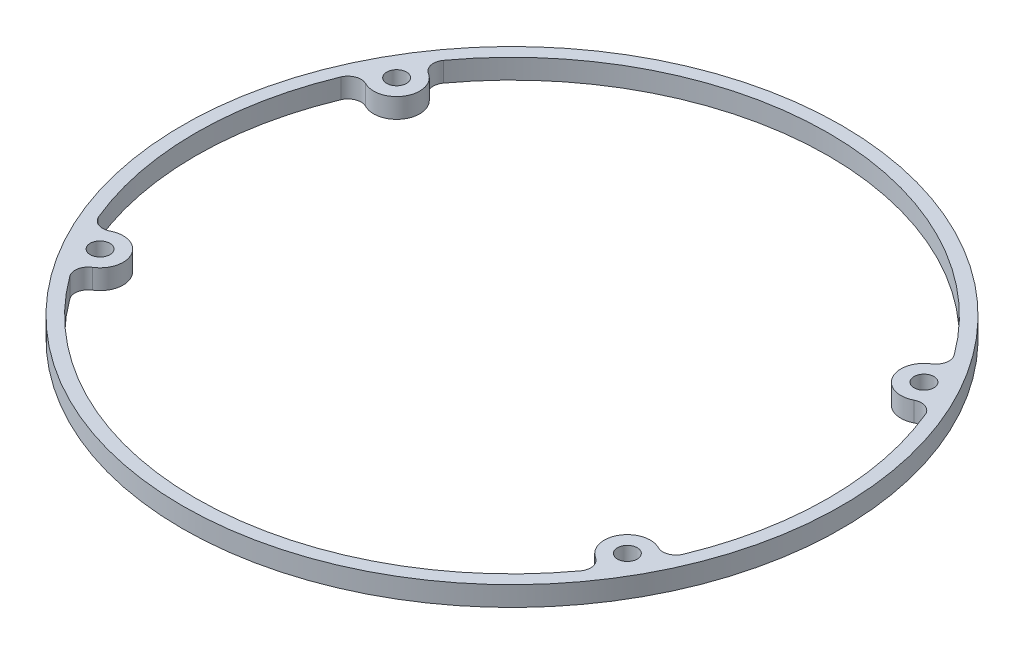
SolidWorks part; units mm, degrees
material "Cast Alloy Steel"
ref_plane "Front Plane" through (0, 0, 0) normal (0, 0, 1) x (1, 0, 0)
ref_plane "Top Plane" through (0, 0, 0) normal (0, 1, 0) x (1, 0, 0)
ref_plane "Right Plane" through (0, 0, 0) normal (1, 0, 0) x (0, 0, -1)
sketch "Sketch1" plane through (0, 0, 0) normal (0, 1, 0) x (1, 0, 0)
  line L1 (40, -22.5) -> (-40, -22.5) construction
  line L2 (40, -22.5) -> (40, 22.5) construction
  line L3 (40, 22.5) -> (-40, 22.5) construction
  line L4 (-40, -22.5) -> (-40, 22.5) construction
  line L5 (40, -22.5) -> (-40, 22.5) construction
  line L6 (40, 22.5) -> (-40, -22.5) construction
  circle A0 centre (0, 0) radius 50
  circle A1 centre (-40, 22.5) radius 1.5
  circle A2 centre (40, 22.5) radius 1.5
  circle A3 centre (40, -22.5) radius 1.5
  circle A4 centre (-40, -22.5) radius 1.5
  dimension "D1" = 100
  dimension "D4" = 3
  dimension "D2" = 80
  dimension "D3" = 45
extrude "Boss-Extrude1" add sketch "Sketch1" along normal blind 3
sketch "Sketch2" plane through (0, 0, 0) normal (0, -1, 0) x (1, 0, 0)
  arc A0 (38.7247, 28.362) -> (-38.7247, 28.362) centre (0, 0) ccw
  circle A1 centre (0, 0) radius 50 construction
  arc A2 (38.1616, 25.4783) -> (41.5906, 19.3823) centre (40, 22.5) ccw
  arc A3 (41.5906, -19.3823) -> (38.1616, -25.4783) centre (40, -22.5) ccw
  arc A4 (-38.1616, -25.4783) -> (-41.5906, -19.3823) centre (-40, -22.5) ccw
  arc A5 (-41.5906, 19.3823) -> (-38.1616, 25.4783) centre (-40, 22.5) ccw
  circle A6 centre (40, 22.5) radius 1.5 construction
  arc A7 (-44.3474, 18.366) -> (-44.3474, -18.366) centre (0, 0) ccw
  arc A8 (-38.7247, -28.362) -> (38.7247, -28.362) centre (0, 0) ccw
  arc A9 (44.3474, -18.366) -> (44.3474, 18.366) centre (0, 0) ccw
  arc A10 (38.1616, -25.4783) -> (38.7247, -28.362) centre (37.1111, -27.1802) cw
  arc A11 (41.5906, -19.3823) -> (44.3474, -18.366) centre (42.4996, -17.6008) ccw
  arc A12 (-38.1616, -25.4783) -> (-38.7247, -28.362) centre (-37.1111, -27.1802) ccw
  arc A13 (-41.5906, -19.3823) -> (-44.3474, -18.366) centre (-42.4996, -17.6008) cw
  arc A14 (-41.5906, 19.3823) -> (-44.3474, 18.366) centre (-42.4996, 17.6008) ccw
  arc A15 (-38.1616, 25.4783) -> (-38.7247, 28.362) centre (-37.1111, 27.1802) cw
  arc A16 (41.5906, 19.3823) -> (44.3474, 18.366) centre (42.4996, 17.6008) cw
  arc A17 (38.1616, 25.4783) -> (38.7247, 28.362) centre (37.1111, 27.1802) ccw
  point P26 (43.1624, -21.0002)
  point P29 (-40.3605, -25.9814)
  point P34 (-43.1624, 21.0002)
  dimension "D1" = 2
  dimension "D2" = 2
  dimension "D3" = 2
extrude "Cut-Extrude1" cut sketch "Sketch2" against normal through all
